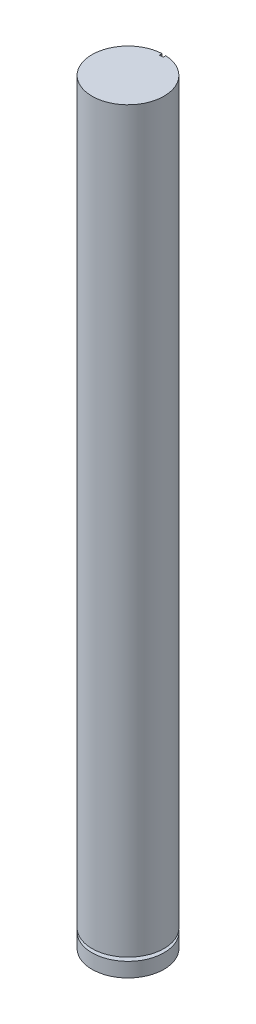
SolidWorks part; units mm, degrees
ref_plane "Front Plane" through (0, 0, 0) normal (0, 0, 1) x (1, 0, 0)
ref_plane "Top Plane" through (0, 0, 0) normal (0, 1, 0) x (1, 0, 0)
ref_plane "Right Plane" through (0, 0, 0) normal (1, 0, 0) x (0, 0, -1)
sketch "Sketch1" plane through (0, 0, 0) normal (0, 1, 0) x (1, 0, 0)
  circle A0 centre (0, 0) radius 2
  dimension "D1" = 4
extrude "Boss-Extrude1" add sketch "Sketch1" along normal blind 42
sketch "Sketch2" plane through (0, 0, 0) normal (1, 0, 0) x (0, 0, -1)
  line L0 (2, 0) -> (2, 42) construction
  line L1 (2, 1) -> (1.5, 1)
  line L2 (2, 1) -> (2, 0.8)
  line L3 (2, 0.8) -> (1.5, 0.8)
  line L4 (1.5, 1) -> (1.5, 0.8)
  line L5 (-2, 0) -> (2, 0) construction
  line L6 (0, 3.0621) -> (0, 0) construction
  dimension "D1" = 0.5
  dimension "D2" = 0.2
  dimension "D3" = 0.8
revolve "Cut-Revolve1" cut sketch "Sketch2" angle 360 about L6
sketch "Sketch3" plane through (0, 42, 0) normal (0, 1, 0) x (1, 0, 0)
  line L0 (0, 2) -> (0, 0) construction
  line L2 (0.1, 2) -> (-0.1, 2)
  line L3 (0.1, 2) -> (0.1, 1.85)
  line L4 (0.1, 1.85) -> (-0.1, 1.85)
  line L5 (-0.1, 2) -> (-0.1, 1.85)
  circle A0 centre (0, 0) radius 2 construction
  dimension "D1" = 0.2
  dimension "D2" = 0.15
extrude "Cut-Extrude1" cut sketch "Sketch3" against normal blind 3
